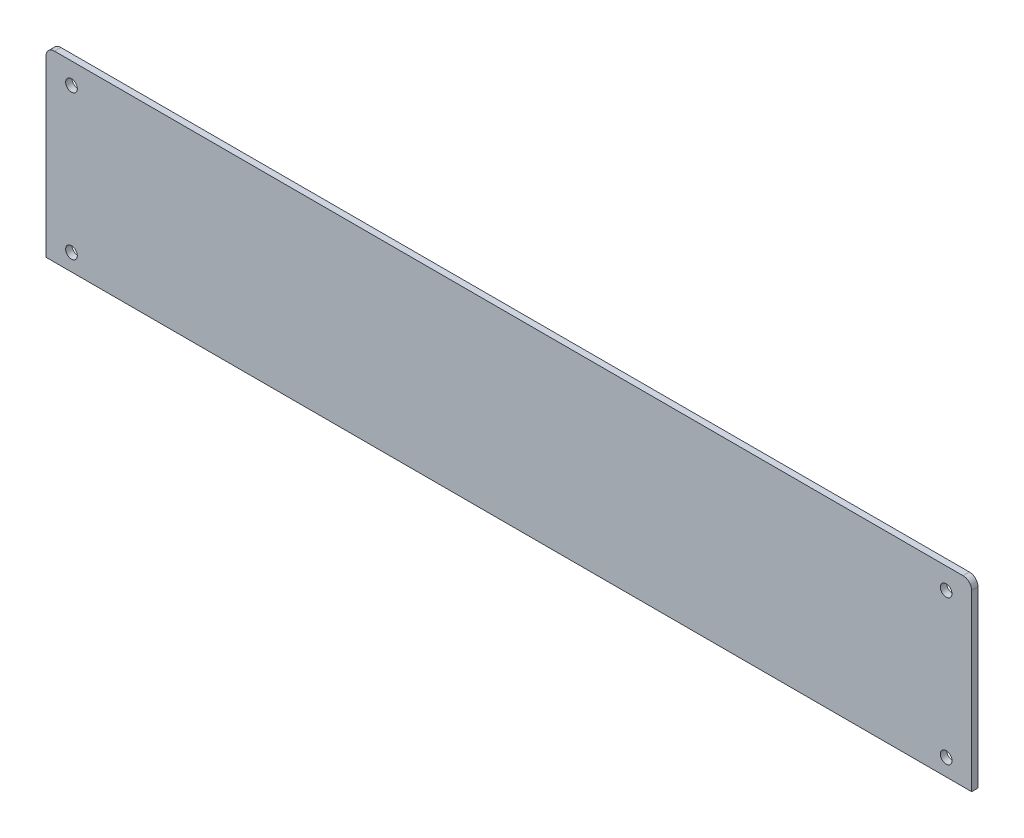
SolidWorks part; units mm, degrees
material "1060 Сплав"
ref_plane "Front" through (0, 0, 0) normal (0, 0, 1) x (1, 0, 0)
ref_plane "Top" through (0, 0, 0) normal (0, 1, 0) x (1, 0, 0)
ref_plane "Right" through (0, 0, 0) normal (1, 0, 0) x (0, 0, -1)
sketch "Эскиз1" plane through (0, 0, 0) normal (0, 0, 1) x (1, 0, 0)
  line L1 (0, 0) -> (436, 0)
  line L2 (0, 0) -> (0, 86.1)
  line L3 (0, 86.1) -> (436, 86.1)
  line L4 (436, 0) -> (436, 86.1)
  point P9 (436, 86.1)
  point P12 (0, 0)
  point P15 (0, 86.1)
  dimension "D1" = 86.1
  dimension "D2" = 436
extrude "Бобышка-Вытянуть1" add sketch "Эскиз1" along normal blind 3
sketch "Эскиз6" plane through (0, 0, 0) normal (0, 0, -1) x (-1, 0, 0)
  line L1 (-436, 0) -> (-436, 86.1) construction
  line L2 (0, 0) -> (-436, 0) construction
  line L5 (0, 86.1) -> (0, 0) construction
  circle A0 centre (-424, 76.1) radius 2.75
  circle A1 centre (-424, 8) radius 2.75
  circle A2 centre (-12, 8) radius 2.75
  circle A3 centre (-12, 76.1) radius 2.75
  dimension "D1" = 12
  dimension "D2" = 5.5
  dimension "D3" = 8
  dimension "D4" = 5.5
  dimension "D5" = 8
  dimension "D6" = 2
  dimension "D8" = 12
extrude "Вырез-Вытянуть1" cut sketch "Эскиз6" against normal through all
fillet "Скругление1" radius 4 2 edges at (0, 86.1, 1.5) (436, 86.1, 1.5)
